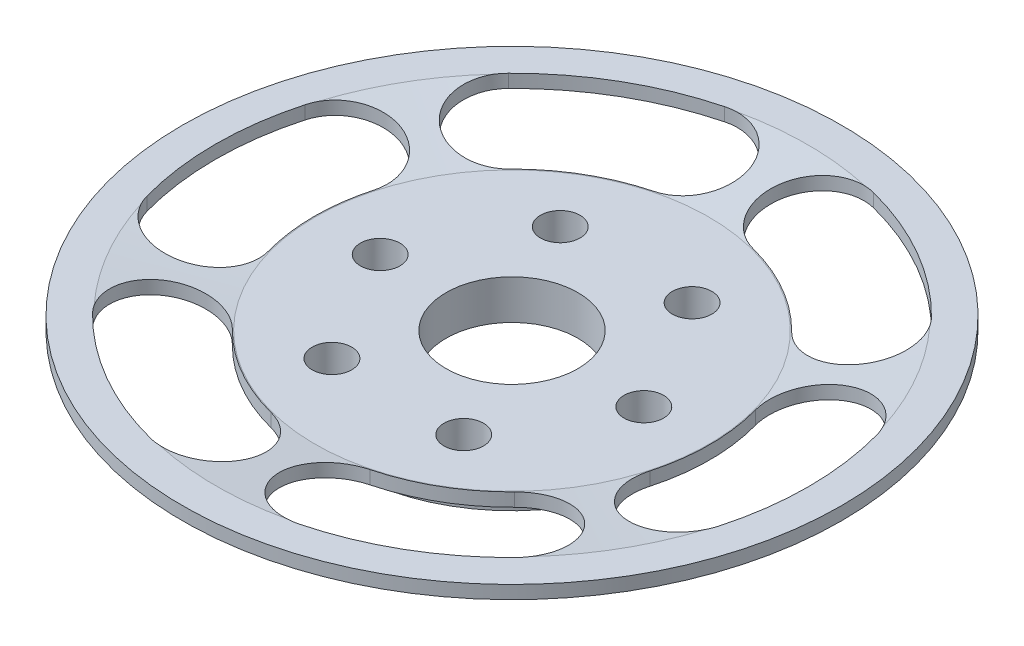
SolidWorks part; units mm, degrees
material "Titanium Ti-8Mn, Annealed"
ref_plane "Front Plane" through (0, 0, 0) normal (0, 0, 1) x (1, 0, 0)
ref_plane "Top Plane" through (0, 0, 0) normal (0, 1, 0) x (1, 0, 0)
ref_plane "Right Plane" through (0, 0, 0) normal (1, 0, 0) x (0, 0, -1)
sketch "Sketch1" plane through (0, 0, 0) normal (0, 0, 1) x (1, 0, 0)
  line L0 (0, -1) -> (0, -37.5174) construction
  line L1 (22.4336, 0) -> (25, 0)
  line L2 (25, 0) -> (25, -1)
  line L3 (25, -1) -> (22.5, -1)
  line L4 (22.5, -1) -> (15, -2)
  line L5 (15, -2) -> (12.5, -2)
  line L6 (12.5, -2) -> (12.5, -4)
  line L7 (12.5, -4) -> (0, -4)
  line L8 (0, -4) -> (0, -1)
  line L9 (22.4336, 0) -> (14.9336, -1)
  line L10 (14.9336, -1) -> (0, -1)
  line L11 (0, 0) -> (25, 0) construction
  line L12 (0, 0) -> (0, -1) construction
  dimension "D1" = 4
  dimension "D2" = 2
  dimension "D3" = 1
  dimension "D4" = 2.5
  dimension "D5" = 25
  dimension "D6" = 50
  dimension "D7" = 2.5
  dimension "D8" = 1
  dimension "D9" = 1
revolve "Revolve1" add sketch "Sketch1" angle 360 about L0
sketch "Sketch2" plane through (0, -2, 0) normal (0, -1, 0) x (1, 0, 0)
  line L0 (0, 0) -> (18.75, 0) construction
  circle A0 centre (0, 0) radius 18.75 construction
  arc A1 (18.071, 5) -> (18.071, -5) centre (0, 0) cw construction
  arc A2 (21.6852, -6) -> (21.6852, 6) centre (0, 0) ccw
  arc A3 (14.4568, -4) -> (14.4568, 4) centre (0, 0) ccw
  arc A4 (14.4568, -4) -> (21.6852, -6) centre (18.071, -5) ccw
  arc A5 (21.6852, 6) -> (14.4568, 4) centre (18.071, 5) ccw
  point P5 (18.75, 0)
  dimension "D1" = 37.5
  dimension "D2" = 3.75
  dimension "D3" = 10
extrude "Cut-Extrude1" cut sketch "Sketch2" against normal up to surface (2 mm away) up to face at (-22.4336, 0, 0)
pattern_circular "CirPattern1" count 6 over 360 about axis through (0, 0, 0) along (0, 1, 0) of "Cut-Extrude1"
sketch "Sketch3" plane through (0, -4, 0) normal (0, -1, 0) x (1, 0, 0)
  circle A0 centre (0, 0) radius 5
  dimension "D1" = 10
extrude "Cut-Extrude2" cut sketch "Sketch3" against normal through all
sketch "Sketch4" plane through (0, -4, 0) normal (0, -1, 0) x (1, 0, 0)
  line L0 (0, 0) -> (10, 0) construction
  circle A0 centre (10, 0) radius 1.5
  dimension "D2" = 3
  dimension "D1" = 10
extrude "Cut-Extrude3" cut sketch "Sketch4" against normal through all
pattern_circular "CirPattern2" count 6 over 360 about axis through (0, 0, 0) along (0, 1, 0) of "Cut-Extrude3"
